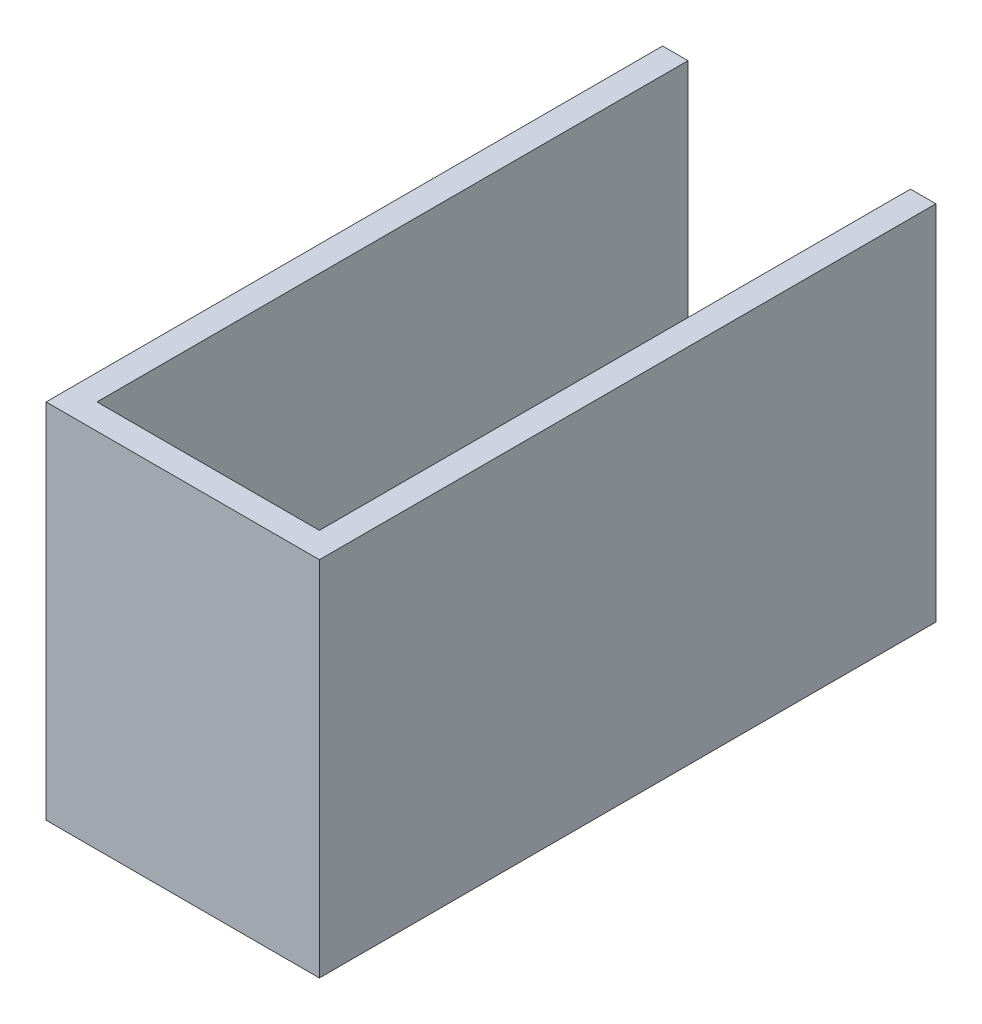
SolidWorks part; units mm, degrees
ref_plane "Front Plane" through (0, 0, 0) normal (0, 0, 1) x (1, 0, 0)
ref_plane "Top Plane" through (0, 0, 0) normal (0, 1, 0) x (1, 0, 0)
ref_plane "Right Plane" through (0, 0, 0) normal (1, 0, 0) x (0, 0, -1)
sketch "Sketch2" plane through (0, 0, 0) normal (0, 0, 1) x (1, 0, 0)
  line L1 (0, 0) -> (21.5, 0)
  line L2 (0, 0) -> (0, 28.5)
  line L3 (0, 28.5) -> (21.5, 28.5)
  line L4 (21.5, 0) -> (21.5, 28.5)
extrude "Boss-Extrude6" add sketch "Sketch2" along normal blind 48.5
sketch3d "3DSketch6"
  line L0 (19.5, 2, 0) -> (19.5, 28.5, 0)
  line L1 (21.5, 28.5, 0) -> (0, 28.5, 0) construction
  line L2 (2, 2, 0) -> (2, 28.5, 0)
  line L3 (19.5, 28.5, 0) -> (2, 28.5, 0)
  line L5 (19.5, 2, 0) -> (2, 2, 0)
extrude "Cut-Extrude5" cut sketch "3DSketch6" along direction (0, 0, -1) on the side of the normal blind 46.5
sketch "Sketch5" plane through (0, 0, 0) normal (0, -1, 0) x (-1, 0, 0)
  circle A0 centre (-10.75, -39.25) radius 1.45
  circle A1 centre (-10.75, -9.25) radius 1.45
  point P11 (-10.75, -24.25)
  dimension "D1" = 2.9
  dimension "D2" = 2.9
  dimension "D3" = 30
extrude "Boss-Extrude7" add sketch "Sketch5" along normal blind 5
